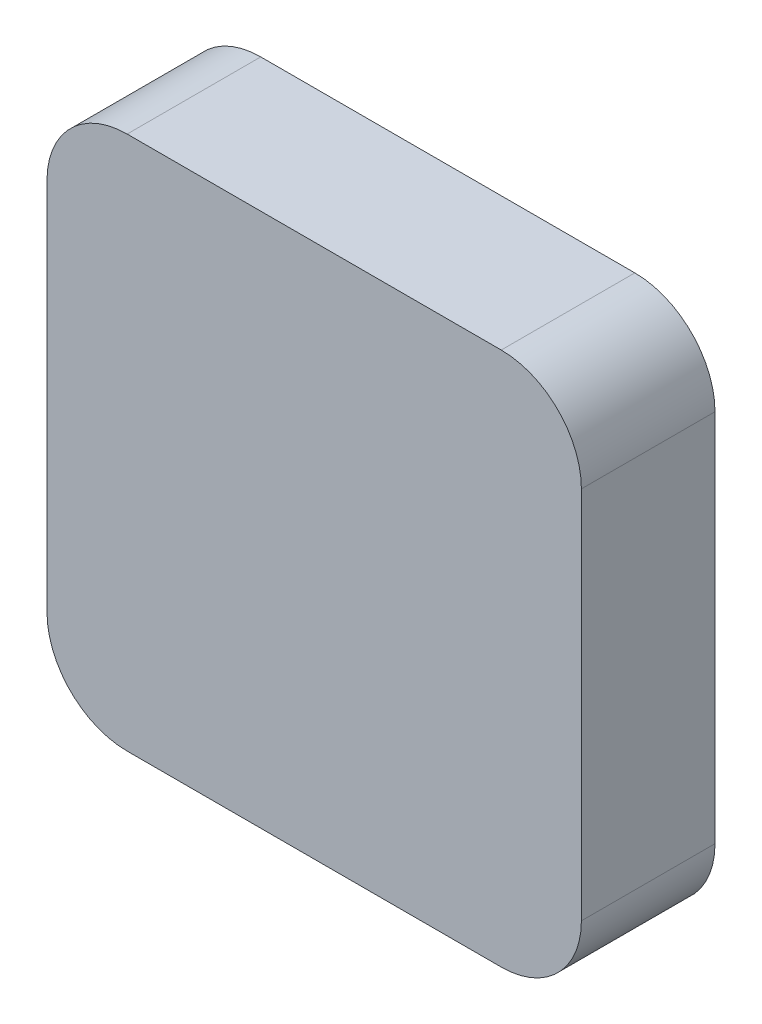
SolidWorks part; units mm, degrees
material "K110"
ref_plane "Front Plane" through (0, 0, 0) normal (0, 0, 1) x (1, 0, 0)
ref_plane "Top Plane" through (0, 0, 0) normal (0, 1, 0) x (1, 0, 0)
ref_plane "Right Plane" through (0, 0, 0) normal (1, 0, 0) x (0, 0, -1)
sketch "Sketch1" plane through (0, 0, 0) normal (0, 0, 1) x (1, 0, 0)
  line L1 (-10, -10) -> (10, -10)
  line L2 (-10, -10) -> (-10, 10)
  line L3 (-10, 10) -> (10, 10)
  line L4 (10, -10) -> (10, 10)
  line L5 (-10, -10) -> (10, 10) construction
  line L6 (-10, 10) -> (10, -10) construction
  point P0 (0, 0)
  dimension "D1" = 20
  dimension "D2" = 20
extrude "Boss-Extrude1" add sketch "Sketch1" along normal mid plane 5
fillet "Fillet1" radius 3 4 edges at (-10, -10, 0) (10, -10, 0) (-10, 10, 0) (10, 10, 0)
